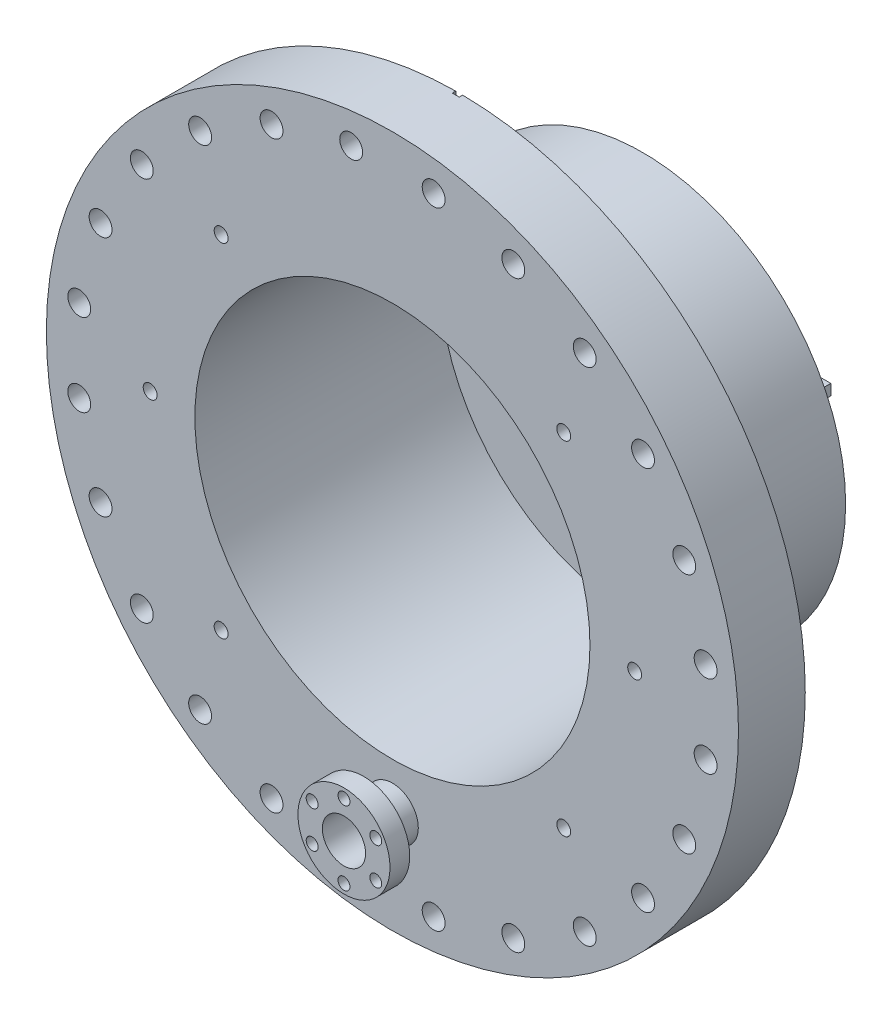
SolidWorks part; units mm, degrees
material "Chrome Stainless Steel"
ref_plane "Front Plane" through (0, 0, 0) normal (0, 0, 1) x (1, 0, 0)
ref_plane "Top Plane" through (0, 0, 0) normal (0, 1, 0) x (1, 0, 0)
ref_plane "Right Plane" through (0, 0, 0) normal (1, 0, 0) x (0, 0, -1)
sketch "Sketch1" plane through (0, 0, 0) normal (0, 0, 1) x (1, 0, 0)
  circle A0 centre (0, 0) radius 74.5
  circle A1 centre (0, 0) radius 72.5
  dimension "D1" = 145
  dimension "D2" = 149
extrude "Extrude1" add sketch "Sketch1" against normal blind 67.31
sketch "Sketch2" plane through (0, 0, 0) normal (0, 0, 1) x (1, 0, 0)
  circle A0 centre (0, 0) radius 72.5
  circle A1 centre (0, 0) radius 127
  circle A2 centre (0, 0) radius 72.5 construction
extrude "Extrude2" add sketch "Sketch2" along normal blind 24.511
sketch "Sketch3" plane through (0, 0, 24.511) normal (0, 0, 1) x (1, 0, 0)
  circle A0 centre (15.1313, -114.9338) radius 4.2
extrude "Cut-Extrude1" cut sketch "Sketch3" against normal up to next
pattern_circular "CirPattern1" count 24 over 360 about axis through (0, 0, 0) along (0, 0, 1) of "Cut-Extrude1"
sketch "Sketch4" plane through (0, 0, -67.31) normal (0, 0, -1) x (-1, 0, 0)
  circle A0 centre (0, 0) radius 74.5
  circle A1 centre (0, 0) radius 32.2
  circle A2 centre (0, 0) radius 74.5 construction
  dimension "D1" = 64.4
extrude "Extrude3" add sketch "Sketch4" against normal blind 2
sketch "Sketch5" plane through (0, 0, 0) normal (0, 1, 0) x (1, 0, 0)
  line L0 (0, 0) -> (0, 106.5628) construction
  line L1 (-32.2, 67.31) -> (-32.2, 55.31)
  line L3 (32.2, 67.31) -> (-32.2, 67.31) construction
  line L4 (74.5, 67.31) -> (-74.5, 67.31) construction
  line L5 (-32.2, 55.31) -> (-31, 55.31)
  line L6 (-31, 55.31) -> (-31, 61.31)
  line L7 (-31, 61.31) -> (-25, 67.31)
  line L8 (-25, 67.31) -> (-32.2, 67.31)
  dimension "D1" = 50
  dimension "D2" = 6
  dimension "D3" = 6
  dimension "D4" = 64.4
  dimension "D5" = 45
revolve "Revolve1" add sketch "Sketch5" angle 360 about L0
sketch "Sketch8" plane through (0, 0, 24.511) normal (0, 0, 1) x (1, 0, 0)
  line L0 (-55, -55) -> (0, 0)
  line L1 (0, 0) -> (-141.2596, 0)
  point P0 (-55, -55)
  dimension "D1" = 45
  dimension "D2" = 55
hole_wizard "#4-40 Tapped Hole1" [suppressed] positions "3DSketch1" profile "Sketch9" tap size "#4-40" standard "Ansi Inch"
sketch3d "3DSketch1"
  point P0 (-55, -55, 24.511)
sketch "Sketch9" plane through (-55, -55, 24.511) normal (1, 0, 0) x (0, -1, 0)
  line L0 (0, 0) -> (0, 8.2992)
  line L1 (0, 8.2992) -> (1.1303, 7.62)
  line L2 (1.1303, 7.62) -> (1.1303, 0)
  line L5 (1.1303, 0) -> (0, 0)
  line L10 (0, 8.2992) -> (-1.1303, 7.62) construction
  line L11 (0, -6.35) -> (0, 107.95) construction
  dimension "Tap Drill Dia." = 2.2606
  dimension "Tap Drill Depth" = 7.62
  dimension "Drill Angle" = 118
cosmetic thread "Hole Thread1" [suppressed] parameters "D1"=5.588, "D2"=2.8448
mirror "Mirror1" [suppressed] about plane through (0, 0, 0) normal (0, 1, 0)
mirror "Mirror2" [suppressed] about plane through (0, 0, 0) normal (1, 0, 0)
sketch "Sketch11" plane through (0, 0, 0) normal (0, 1, 0) x (1, 0, 0)
  line L0 (-31.7, 67.31) -> (-31.7, 61.3171)
  line L1 (-25, 67.31) -> (-32.2, 67.31) construction
  line L2 (-31.7, 61.3171) -> (-25.7071, 67.31)
  line L3 (-25.7071, 67.31) -> (-31.7, 67.31)
  line L4 (-31, 61.31) -> (-25, 67.31) construction
  line L5 (-32.2, 67.31) -> (-32.2, 55.31) construction
  dimension "D1" = 0.5
  dimension "D2" = 0.5
revolve "Cut-Revolve1" cut sketch "Sketch11" angle 360 about L0
sketch "RF Feedtrhough angle and distance sketch" plane through (0, 0, 24.511) normal (0, 0, 1) x (1, 0, 0)
  line L0 (0, 0) -> (0, 136.8547) construction
  line L1 (0, 0) -> (0, -153.071) construction
  circle A0 centre (0, 0) radius 89.535 construction
  point P3 (0, -89.535)
  dimension "D2" = 179.07
  dimension "D1" = 180
ref_plane "Rf Feedthrough flange plane" through (0, 0, 42.291) normal (0, 0, 1) x (1, 0, 0)
sketch "Sketch13" plane through (0, 0, 42.291) normal (0, 0, 1) x (1, 0, 0)
  circle A0 centre (0, -89.535) radius 7.9375
  dimension "D1" = 15.875
extrude "Extrude4" cut sketch "Sketch13" against normal through all
sketch "Sketch14" plane through (0, 0, 42.291) normal (0, 0, 1) x (1, 0, 0)
  circle A0 centre (0, -89.535) radius 7.9375
  circle A1 centre (0, -89.535) radius 9.4996
  dimension "D1" = 18.9992
extrude "Extrude5" add sketch "Sketch14" against normal up to surface (17.78 mm away) up to face at (7.9375, -89.535, 24.511)
sketch "Sketch15" plane through (0, 0, 42.291) normal (0, 0, 1) x (1, 0, 0)
  circle A0 centre (0, -89.535) radius 7.9375
  circle A1 centre (0, -89.535) radius 16.891
  dimension "D1" = 33.782
extrude "Extrude6" add sketch "Sketch15" against normal blind 7.239
sketch "Sketch16" plane through (0, 0, 42.291) normal (0, 0, 1) x (1, 0, 0)
  line L0 (0, 0) -> (0, -89.535) construction
  circle A0 centre (0, -76.0476) radius 2.1844
  dimension "D1" = 4.3688
  dimension "D2" = 13.4874
extrude "Extrude7" cut sketch "Sketch16" against normal blind 7.239
pattern_circular "CirPattern2" count 6 over 360 about axis through (0, -89.535, 0) along (0, 0, 1) of "Extrude7"
sketch "Sketch17" plane through (0, 0, -67.31) normal (0, 0, -1) x (-1, 0, 0)
  line L0 (0, -40.1853) -> (0, 59.5552) construction
  line L1 (-61.4294, -24.0115) -> (-54.5706, -24.0115)
  line L2 (-61.4294, -24.0115) -> (-61.4294, -27.9885)
  line L3 (-61.4294, -27.9885) -> (-54.5706, -27.9885)
  line L4 (-54.5706, -24.0115) -> (-54.5706, -27.9885)
  line L5 (0, 0) -> (-65.9154, 0) construction
  line L6 (-58, -27.9885) -> (-58, -24.0115) construction
  line L7 (-61.4294, -26) -> (-54.5706, -26) construction
  dimension "D1" = 58
  dimension "D2" = 26
extrude "Extrude8" add sketch "Sketch17" along normal blind 7.62
mirror "Mirror3" about plane through (0, 0, 0) normal (0, 1, 0) of "Extrude8"
mirror "Mirror4" about plane through (0, 0, 0) normal (1, 0, 0) of "Extrude8", "Mirror3"
sketch "Sketch18" plane through (0, 0, 24.511) normal (0, 0, 1) x (1, 0, 0)
  line L0 (0, 0) -> (92.2033, 0) construction
  line L1 (0, 0) -> (0, -117.955) construction
  line L2 (63.3193, -63.3193) -> (0, 0) construction
  circle A0 centre (0, 0) radius 88.9 construction
  point P6 (88.9, 0)
  point P7 (62.8618, -62.8618)
  point P8 (62.8618, 62.8618)
  point P11 (-88.9, 0)
  point P12 (-62.8618, 62.8618)
  point P13 (-62.8618, -62.8618)
  dimension "D2" = 177.8
  dimension "D1" = 45
hole_wizard "1/4-20 Tapped Hole1" positions "3DSketch3" profile "Sketch20" tap size "1/4-20" standard "Ansi Inch"
sketch3d "3DSketch3"
  point P0 (62.8618, -62.8618, 24.511)
  point P3 (-62.8618, -62.8618, 24.511)
  point P6 (-88.9, 0, 24.511)
  point P9 (-62.8618, 62.8618, 24.511)
  point P12 (62.8618, 62.8618, 24.511)
  point P15 (88.9, 0, 24.511)
sketch "Sketch20" plane through (62.8618, -62.8618, 24.511) normal (1, 0, 0) x (0, -1, 0)
  line L0 (0, 0) -> (0, 14.2338)
  line L1 (0, 14.2338) -> (2.5527, 12.7)
  line L2 (2.5527, 12.7) -> (2.5527, 0)
  line L5 (2.5527, 0) -> (0, 0)
  line L10 (0, 14.2338) -> (-2.5527, 12.7) construction
  line L11 (0, -6.35) -> (0, 107.95) construction
  dimension "Tap Drill Dia." = 5.1054
  dimension "Tap Drill Depth" = 12.7
  dimension "Drill Angle" = 118
cosmetic thread "Hole Thread2" parameters "D1"=12.7, "D2"=6.35
cosmetic thread "Hole Thread3" parameters "D1"=12.7, "D2"=6.35
cosmetic thread "Hole Thread4" parameters "D1"=12.7, "D2"=6.35
cosmetic thread "Hole Thread5" parameters "D1"=12.7, "D2"=6.35
cosmetic thread "Hole Thread6" parameters "D1"=12.7, "D2"=6.35
cosmetic thread "Hole Thread7" parameters "D1"=12.7, "D2"=6.35
sketch "Sketch21" plane through (0, 0, 0) normal (0, 0, -1) x (-1, 0, 0)
  line L0 (0, 0) -> (-151.7789, 0) construction
  line L1 (0, 0) -> (0, -14.4551) construction
  line L2 (1.27, -132.9872) -> (-1.27, -132.9872)
  line L3 (-1.27, -132.9872) -> (-1.27, -105.5225)
  line L4 (-1.27, -105.5225) -> (1.27, -105.5225)
  line L5 (1.27, -132.9872) -> (1.27, -105.5225)
  line L6 (1.27, 132.9872) -> (1.27, 105.5225)
  line L7 (-1.27, 105.5225) -> (1.27, 105.5225)
  line L8 (-1.27, 132.9872) -> (-1.27, 105.5225)
  line L9 (1.27, 132.9872) -> (-1.27, 132.9872)
  point P10 (0, 105.5225)
  point P11 (0, -132.9872)
  point P12 (0, -105.5225)
  point P13 (0, 132.9872)
  dimension "D1" = 2.54
extrude "Extrude9" cut sketch "Sketch21" against normal blind 1.27
